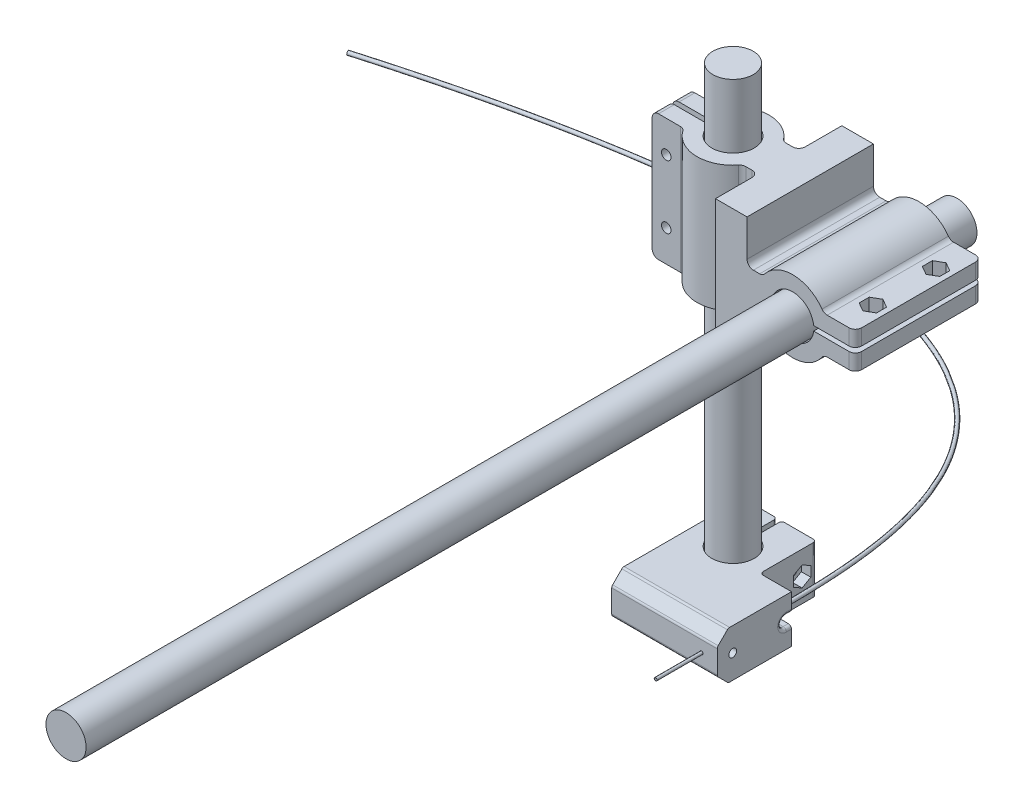
SolidWorks part; units mm, degrees
ref_plane "Front Plane" through (0, 0, 0) normal (0, 0, 1) x (1, 0, 0)
ref_plane "Top Plane" through (0, 0, 0) normal (0, 1, 0) x (1, 0, 0)
ref_plane "Right Plane" through (0, 0, 0) normal (1, 0, 0) x (0, 0, -1)
sketch "Sketch1" plane through (0, 0, 0) normal (0, 1, 0) x (1, 0, 0)
  circle A0 centre (0, 0) radius 6.4
  dimension "D1" = 12.8
extrude "Boss-Extrude1" add sketch "Sketch1" along normal blind 40 and the other way blind 100
sketch "Sketch2" plane through (0, 0, 0) normal (0, 1, 0) x (1, 0, 0)
  line L0 (-9.8437, 5.75) -> (-19.8437, 5.75)
  line L1 (-19.8437, 5.75) -> (-19.8437, 0.75)
  line L2 (0, 6.4) -> (0, 0) construction
  line L3 (-39.5441, 0) -> (14.434, 0) construction
  line L4 (9.434, -6.4) -> (14.434, -6.4)
  line L5 (-19.8437, 0.75) -> (-6.6579, 0.75)
  line L6 (-19.8437, -0.75) -> (-6.6579, -0.75)
  line L7 (-19.8437, -5.75) -> (-19.8437, -0.75)
  line L8 (-9.8437, -5.75) -> (-19.8437, -5.75)
  line L9 (14.434, -6.4) -> (14.434, 6.4)
  line L10 (14.434, 6.4) -> (9.434, 6.4)
  arc A0 (9.434, 6.4) -> (-9.8437, 5.75) centre (0, 0) ccw
  circle A1 centre (0, 0) radius 6.4 construction
  arc A2 (-6.6579, -0.75) -> (-6.6579, 0.75) centre (0, 0) ccw
  arc A3 (9.434, -6.4) -> (-9.8437, -5.75) centre (0, 0) cw
  point P13 (0, 3.2)
  point P20 (0, -3.2)
  point P21 (6.7, 0)
  dimension "D1" = 5
  dimension "D2" = 0.3
  dimension "D6" = 5
  dimension "D3" = 0.75
  dimension "D4" = 5
  dimension "D5" = 10
extrude "Boss-Extrude2" add sketch "Sketch2" along normal blind 20 and the other way blind 20 separate body
sketch "Sketch6" plane through (14.434, 0, 0) normal (1, 0, 0) x (0, 0, -1)
  line L0 (-6.4, -20) -> (6.4, -20) construction
  line L1 (-20, -20) -> (20, -20)
  line L2 (-20, -20) -> (-20, 20)
  line L3 (-20, 20) -> (20, 20)
  line L4 (20, -20) -> (20, 20)
  line L5 (-20, -20) -> (20, 20) construction
  line L6 (-20, 20) -> (20, -20) construction
  point P0 (0, 0)
  dimension "D1" = 40
extrude "Boss-Extrude6" add sketch "Sketch6" along normal blind 10
ref_plane "Plane1" through (0, 0, 0) normal (0, 0, -1) x (-1, 0, 0)
sketch "Sketch7" plane through (0, 0, 0) normal (0, 0, -1) x (-1, 0, 0)
  line L0 (0, 0) -> (-105.5276, 0) construction
  line L1 (-24.434, -6.4) -> (-29.434, -6.4)
  line L3 (-24.434, 20) -> (-24.434, -20) construction
  line L4 (-48.7116, -5.75) -> (-58.7116, -5.75)
  line L5 (-58.7116, -5.75) -> (-58.7116, -0.75)
  line L6 (-58.7116, -0.75) -> (-45.5259, -0.75)
  line L7 (-24.434, -6.4) -> (-24.434, 6.4)
  line L8 (-58.7116, 0.75) -> (-45.5259, 0.75)
  line L9 (-58.7116, 5.75) -> (-58.7116, 0.75)
  line L10 (-48.7116, 5.75) -> (-58.7116, 5.75)
  line L11 (-24.434, 6.4) -> (-29.434, 6.4)
  circle A0 centre (-38.868, 0) radius 6.4 construction
  arc A1 (-48.7116, -5.75) -> (-29.434, -6.4) centre (-38.868, 0) ccw
  arc A2 (-45.5259, -0.75) -> (-45.5259, 0.75) centre (-38.868, 0) ccw
  arc A3 (-48.7116, 5.75) -> (-29.434, 6.4) centre (-38.868, 0) cw
  point P15 (-38.868, -6.4)
  point P19 (-24.434, 0)
  point P21 (-38.868, 6.4)
  dimension "D1" = 12.8
  dimension "D2" = 5
  dimension "D4" = 0.3
  dimension "D7" = 10
  dimension "D3" = 5
  dimension "D5" = 0.75
  dimension "D6" = 5
extrude "Boss-Extrude7" add sketch "Sketch7" along normal blind 20 and the other way blind 20
fillet "Fillet4" radius 2 4 edges
fillet "Fillet5" radius 2 8 edges at (29.434, -6.4, 0) (29.434, 6.4, 0) (48.7116, 5.75, 0) (48.7116, -5.75, 0) (9.434, 0, 6.4) (9.434, 0, -6.4) (-9.8437, 0, -5.75) (-9.8437, 0, 5.75)
sketch "Sketch9" plane through (0, 0, 5.75) normal (0, 0, 1) x (1, 0, 0)
  line L0 (-10.9315, 0) -> (-19.8437, 0) construction
  line L1 (-19.8437, -20) -> (-19.8437, 20) construction
  line L2 (-15.3876, 0) -> (-15.3876, -20) construction
  line L3 (-10.9315, -20) -> (-10.9315, 20) construction
  line L4 (-19.8437, -20) -> (-10.9315, -20) construction
  circle A0 centre (-15.3876, -10) radius 1.5
  circle A1 centre (-15.3876, 0) radius 2.5 construction
  circle A2 centre (-15.3876, 10) radius 1.5
  dimension "D1" = 5
  dimension "D2" = 3
extrude "Cut-Extrude1" cut sketch "Sketch9" against normal up to surface (11.5 mm away) up to face at (-15.3876, 0, -5.75)
sketch "Sketch37" plane through (0, 0, -5.75) normal (0, 0, -1) x (-1, 0, 0)
  line L0 (18.1376, -8.4123) -> (18.1376, -11.5877)
  line L1 (12.6376, -8.4123) -> (12.6376, -11.5877)
  line L2 (18.1376, -8.4123) -> (15.3876, -6.8246)
  line L3 (15.3876, -6.8246) -> (12.6376, -8.4123)
  line L4 (12.6376, -11.5877) -> (15.3876, -13.1754)
  line L5 (15.3876, -13.1754) -> (18.1376, -11.5877)
  line L6 (12.6376, -10) -> (18.1376, -10) construction
  line L8 (10.9315, 0) -> (19.8437, 0) construction
  line L9 (10.9315, 20) -> (10.9315, -20) construction
  line L10 (19.8437, -20) -> (19.8437, 20) construction
  line L11 (12.6376, 10) -> (18.1376, 10) construction
  line L12 (15.3876, 13.1754) -> (18.1376, 11.5877)
  line L13 (12.6376, 11.5877) -> (15.3876, 13.1754)
  line L14 (15.3876, 6.8246) -> (12.6376, 8.4123)
  line L15 (18.1376, 8.4123) -> (15.3876, 6.8246)
  line L16 (12.6376, 8.4123) -> (12.6376, 11.5877)
  line L17 (18.1376, 8.4123) -> (18.1376, 11.5877)
  circle A0 centre (15.3876, -10) radius 1.25
  circle A6 centre (15.3876, -10) radius 1.5 construction
  circle A7 centre (15.3876, 10) radius 1.25
  dimension "D2" = 120
  dimension "D3" = 2.5
  dimension "D1" = 5.5
  dimension "D4" = 2.75
extrude "Cut-Extrude24" cut sketch "Sketch37" against normal up to surface (5 mm away) up to face at (-13.8876, 10, -0.75)
sketch "Sketch10" plane through (0, -5.75, 0) normal (0, -1, 0) x (-1, 0, 0)
  line L0 (-58.7116, 0) -> (-49.7995, 0) construction
  line L1 (-58.7116, -20) -> (-58.7116, 20) construction
  line L2 (-49.7995, -20) -> (-49.7995, 20) construction
  line L3 (-54.2555, 0) -> (-54.2555, 20) construction
  line L4 (-58.7116, 20) -> (-49.7995, 20) construction
  circle A0 centre (-54.2555, 0) radius 2.5 construction
  circle A1 centre (-54.2555, 10) radius 2.5
  circle A2 centre (-54.2555, -10) radius 2.5
  dimension "D1" = 5
  dimension "D2" = 5
extrude "Cut-Extrude2" cut sketch "Sketch10" against normal up to surface (11.5 mm away) up to face at (54.2555, 5.75, 0)
sketch "Sketch38" plane through (0, 5.75, 0) normal (0, 1, 0) x (1, 0, 0)
  line L0 (57.0055, 11.5877) -> (57.0055, 8.4123)
  line L1 (51.5055, 11.5877) -> (51.5055, 8.4123)
  line L2 (57.0055, 11.5877) -> (54.2555, 13.1754)
  line L3 (54.2555, 13.1754) -> (51.5055, 11.5877)
  line L4 (51.5055, 8.4123) -> (54.2555, 6.8246)
  line L5 (54.2555, 6.8246) -> (57.0055, 8.4123)
  line L6 (57.0055, 10) -> (51.5055, 10) construction
  line L7 (58.7116, 0) -> (49.7995, 0) construction
  line L8 (58.7116, -20) -> (58.7116, 20) construction
  line L9 (49.7995, 20) -> (49.7995, -20) construction
  line L10 (57.0055, -10) -> (51.5055, -10) construction
  line L11 (54.2555, -6.8246) -> (57.0055, -8.4123)
  line L12 (51.5055, -8.4123) -> (54.2555, -6.8246)
  line L13 (54.2555, -13.1754) -> (51.5055, -11.5877)
  line L14 (57.0055, -11.5877) -> (54.2555, -13.1754)
  line L15 (51.5055, -11.5877) -> (51.5055, -8.4123)
  line L16 (57.0055, -11.5877) -> (57.0055, -8.4123)
  circle A0 centre (54.2555, 10) radius 1.25
  circle A1 centre (54.2555, 10) radius 2.5 construction
  circle A2 centre (54.2555, -10) radius 1.25
  dimension "D3" = 2.5
  dimension "D1" = 5.5
  dimension "D2" = 120
  dimension "D4" = 2.75
extrude "Cut-Extrude25" cut sketch "Sketch38" against normal up to surface (5 mm away) up to face at (56.7555, 0.75, 10)
fillet "Fillet12" radius 2 8 edges at (-19.8437, 20, 3.25) (-19.8437, -20, 3.25) (-19.8437, 20, -3.25) (-19.8437, -20, -3.25) (58.7116, -3.25, -20) (58.7116, -3.25, 20) (58.7116, 3.25, -20) (58.7116, 3.25, 20)
sketch "Sketch13" plane through (0, -100, 0) normal (0, -1, 0) x (1, 0, 0)
  line L0 (11.7, -14.6579) -> (11.7, 26.7)
  line L1 (11.7, -14.6579) -> (0.75, -14.6579)
  line L2 (0, -14.6579) -> (0, 33.0338) construction
  line L3 (-11.7, 26.7) -> (11.7, 26.7)
  line L5 (0.75, -14.6579) -> (0.75, -6.6579)
  line L6 (-0.75, -14.6579) -> (-0.75, -6.6579)
  line L8 (-11.7, -14.6579) -> (-0.75, -14.6579)
  line L9 (-11.7, -14.6579) -> (-11.7, 26.7)
  arc A0 (0.75, -6.6579) -> (-0.75, -6.6579) centre (0, 0) ccw
  circle A1 centre (0, 0) radius 6.4 construction
  point P13 (6.7, 0)
  point P18 (-6.7, 0)
  point P19 (0, 6.7)
  dimension "D1" = 0.3
  dimension "D4" = 5
  dimension "D2" = 0.75
  dimension "D3" = 8
  dimension "D5" = 20
extrude "Boss-Extrude8" add sketch "Sketch13" along normal blind 7.5 and the other way blind 7.5 separate body
sketch "Sketch22" [suppressed] plane through (0, -92.5, 0) normal (0, 1, 0) x (1, 0, 0)
  line L0 (-3, -26.7) -> (-11.7, -18) construction
  line L1 (3, -26.7) -> (-3, -26.7) construction
  line L2 (11.7, -18) -> (3, -26.7) construction
  line L3 (-3, -26.7) -> (-11.7, -18)
  line L4 (3, -26.7) -> (-3, -26.7)
  line L5 (11.7, -18) -> (3, -26.7)
  line L6 (-11.7, -18) -> (-11.7, -10.7)
  line L7 (-11.7, -26.7) -> (-11.7, 14.6579) construction
  line L8 (-11.7, -10.7) -> (11.7, -10.7)
  line L9 (11.7, 14.6579) -> (11.7, -26.7) construction
  line L10 (11.7, -10.7) -> (11.7, -18)
  arc A1 (-0.75, 6.6579) -> (0.75, 6.6579) centre (0, 0) ccw construction
  point P10 (0, -6.7)
  dimension "D1" = 4
extrude "Boss-Extrude10" [suppressed] add sketch "Sketch22" along normal blind 10
sketch "Sketch23" [suppressed] plane through (0, 0, 10.7) normal (0, 0, -1) x (-1, 0, 0)
  line L0 (0, -75) -> (0, -65) construction
  line L1 (-11.7, -75) -> (11.7, -75) construction
  line L2 (-11.7, -65) -> (11.7, -65) construction
  line L3 (-11.7, -65) -> (-11.7, -75) construction
  circle A0 centre (0, -70) radius 0.5
  dimension "D1" = 1
extrude "Cut-Extrude11" [suppressed] cut sketch "Sketch23" against normal up to next
sketch "Sketch24" [suppressed] plane through (0, 0, 10.7) normal (0, 0, -1) x (-1, 0, 0)
  circle A0 centre (0, -70) radius 1.75
  dimension "D1" = 3.5
extrude "Cut-Extrude12" [suppressed] cut sketch "Sketch24" against normal blind 8
sketch "Sketch25" [suppressed] plane through (0, -65, 0) normal (0, 1, 0) x (1, 0, 0)
  line L0 (0, -26.7) -> (0, -18.7) construction
  line L1 (-3, -26.7) -> (3, -26.7) construction
  line L2 (1.75, -18.7) -> (-1.75, -18.7) construction
  circle A0 centre (0, -22.7) radius 1.45
  dimension "D1" = 2.9
extrude "Cut-Extrude13" [suppressed] cut sketch "Sketch25" against normal blind 5
sketch "Sketch26" [suppressed] plane through (0, -62.5, 0) normal (0, 1, 0) x (1, 0, 0)
  line L0 (0, -5.5763) -> (0, -13.6517) construction
  line L2 (1.75, -5.5763) -> (1.75, -13.6517)
  line L4 (-1.75, -5.5763) -> (-1.75, -13.6517)
  arc A0 (1.75, -5.5763) -> (-1.75, -5.5763) centre (0, -5.5763) ccw
  arc A1 (-1.75, -13.6517) -> (1.75, -13.6517) centre (0, -13.6517) ccw
  point P5 (0, -9.614)
  dimension "D1" = 3.5
extrude "Cut-Extrude14" [suppressed] cut sketch "Sketch26" against normal blind 5
fillet "Fillet6" radius 1 2 edges at (-11.7, -100, -14.6579) (11.7, -100, -14.6579)
fillet "Fillet7" radius 1 2 edges at (0.75, -100, -14.6579) (-0.75, -100, -14.6579)
sketch "Sketch17" plane through (-11.7, 0, 0) normal (-1, 0, 0) x (0, 0, 1)
  line L0 (-13.6579, -100) -> (-6.6579, -100) construction
  line L3 (-6.6579, -92.5) -> (-6.6579, -107.5) construction
  line L4 (-13.6579, -92.5) -> (-13.6579, -107.5) construction
  circle A0 centre (-10.1579, -100) radius 1.55
  dimension "D1" = 3.1
extrude "Cut-Extrude8" cut sketch "Sketch17" against normal up to surface (23.4 mm away) up to face at (11.7, -100, 6.5211)
sketch "Sketch18" plane through (11.7, 0, 0) normal (1, 0, 0) x (0, 0, -1)
  line L0 (12.9079, -98.4123) -> (12.9079, -101.5877)
  line L1 (7.4079, -98.4123) -> (7.4079, -101.5877)
  line L2 (12.9079, -98.4123) -> (10.1579, -96.8246)
  line L3 (10.1579, -96.8246) -> (7.4079, -98.4123)
  line L4 (7.4079, -101.5877) -> (10.1579, -103.1754)
  line L5 (10.1579, -103.1754) -> (12.9079, -101.5877)
  line L6 (12.9079, -100) -> (7.4079, -100) construction
  circle A0 centre (10.1579, -100) radius 1.25 construction
  circle A1 centre (10.1579, -100) radius 1.55 construction
  dimension "D3" = 2.5
  dimension "D1" = 5.5
  dimension "D2" = 120
  dimension "D4" = 2.75
extrude "Cut-Extrude9" cut sketch "Sketch18" against normal blind 3
sketch "Sketch19" plane through (0, -100, 0) normal (0, -1, 0) x (-1, 0, 0)
  circle A1 centre (0, 0) radius 6.4
  circle A2 centre (0, 0) radius 6.4
  dimension "D1" = 0
extrude "Boss-Extrude9" add sketch "Sketch19" along normal blind 20
fillet "Fillet9" [suppressed] radius 1
sketch "Sketch27" plane through (11.7, 0, 0) normal (1, 0, 0) x (0, 0, -1)
  line L0 (-26.7, -100) -> (13.6579, -100) construction
  line L3 (-26.7, -92.5) -> (-26.7, -107.5) construction
  line L4 (13.6579, -107.5) -> (13.6579, -92.5) construction
  line L5 (-23.2, -92.5) -> (-26.7, -96)
  line L6 (13.6579, -92.5) -> (-26.7, -92.5) construction
  line L7 (-26.7, -96) -> (-26.7, -104)
  line L8 (-23.2, -92.5) -> (-3.2, -92.5)
  line L9 (-3.2, -92.5) -> (-3.2, -107.5)
  line L10 (-23.2, -107.5) -> (-3.2, -107.5)
  line L11 (-23.2, -107.5) -> (-26.7, -104)
  point P13 (-3.2, -100)
  dimension "D1" = 45
  dimension "D2" = 20
  dimension "D3" = 4
extrude "Boss-Extrude11" add sketch "Sketch27" along normal blind 10
sketch "Sketch28" plane through (11.7, 0, 0) normal (1, 0, 0) x (0, 0, -1)
  line L0 (-26.7, -92.5) -> (-26.7, -96) construction
  line L1 (-26.7, -96) -> (-23.2, -92.5) construction
  line L2 (-23.2, -92.5) -> (-26.7, -92.5) construction
  line L3 (-26.7, -107.5) -> (-23.2, -107.5) construction
  line L4 (-23.2, -107.5) -> (-26.7, -104) construction
  line L5 (-26.7, -104) -> (-26.7, -107.5) construction
  line L6 (-26.7, -92.5) -> (-26.7, -96)
  line L7 (-26.7, -96) -> (-23.2, -92.5)
  line L8 (-23.2, -92.5) -> (-26.7, -92.5)
  line L9 (-26.7, -107.5) -> (-23.2, -107.5)
  line L10 (-23.2, -107.5) -> (-26.7, -104)
  line L11 (-26.7, -104) -> (-26.7, -107.5)
extrude "Cut-Extrude15" cut sketch "Sketch28" against normal up to next (23.4 mm away)
sketch "Sketch29" plane through (0, 0, 3.2) normal (0, 0, -1) x (-1, 0, 0)
  line L0 (-11.7, -100) -> (-21.7, -100) construction
  line L1 (-11.7, -107.5) -> (-11.7, -92.5) construction
  line L2 (-21.7, -107.5) -> (-21.7, -92.5) construction
  circle A0 centre (-16.7, -100) radius 0.5
  dimension "D1" = 1
extrude "Cut-Extrude16" cut sketch "Sketch29" against normal up to next (23.5 mm away)
sketch "Sketch30" plane through (0, 0, 3.2) normal (0, 0, -1) x (-1, 0, 0)
  circle A0 centre (-16.7, -100) radius 1.75
  dimension "D1" = 3.5
extrude "Cut-Extrude17" cut sketch "Sketch30" against normal blind 8
fillet "Fillet10" radius 1 5 edges at (5, -107.5, 23.2) (5, -104, 26.7) (5, -96, 26.7) (5, -92.5, 23.2) (11.7, -100, 3.2)
sketch "Sketch31" plane through (21.7, 0, 0) normal (1, 0, 0) x (0, 0, -1)
  line L0 (-3.2, -100) -> (-26.7, -100) construction
  line L1 (-3.2, -107.5) -> (-3.2, -92.5) construction
  line L2 (-26.7, -96.4142) -> (-26.7, -103.5858) construction
  circle A0 centre (-21.7969, -100) radius 1.25
  dimension "D1" = 2.5
extrude "Cut-Extrude18" cut sketch "Sketch31" against normal blind 5
sketch "Sketch32" plane through (21.7, 0, 0) normal (1, 0, 0) x (0, 0, -1)
  line L0 (-1.5811, -100) -> (-4.8189, -100) construction
  line L1 (-3.2, -107.5) -> (-3.2, -92.5) construction
  line L2 (-1.5811, -101.75) -> (-4.8189, -101.75)
  line L3 (-1.5811, -98.25) -> (-4.8189, -98.25)
  arc A0 (-1.5811, -101.75) -> (-1.5811, -98.25) centre (-1.5811, -100) ccw
  arc A1 (-4.8189, -98.25) -> (-4.8189, -101.75) centre (-4.8189, -100) ccw
  point P4 (-3.2, -100)
  dimension "D1" = 3.5
extrude "Cut-Extrude19" cut sketch "Sketch32" against normal blind 5
fillet "Fillet11" radius 1 3 edges at (21.7, -101.75, 4.0095) (21.7, -100, 6.5689) (21.7, -98.25, 4.0095)
sketch "Sketch39" plane through (0, 0, 0) normal (0, 0, 1) x (1, 0, 0)
  circle A0 centre (38.868, 0) radius 6.35
  dimension "D1" = 12.7
extrude "Boss-Extrude12" add sketch "Sketch39" along normal blind 250 and the other way blind 32 separate body
ref_plane "Plane3" through (0, -100, 0) normal (0, 1, 0) x (1, 0, 0)
sketch "Sketch41" plane through (0, 0, 11.2) normal (0, 0, -1) x (-1, 0, 0)
  circle A0 centre (-16.7, -100) radius 0.4
  circle A1 centre (-16.7, -100) radius 0.45
  dimension "D1" = 0.05
  dimension "D2" = 0.8
extrude "Boss-Extrude13" add sketch "Sketch41" against normal blind 30 and the other way blind 10 separate body
sketch "Sketch42" plane through (0, -100, 0) normal (0, 1, 0) x (1, 0, 0)
  line L0 (17.15, -1.2) -> (16.25, -1.2) construction
  spline S0 degree 3 poles (17.2, -11.2) (17.2, 4.4788) (20.203, 78.2682) (-56.3752, 124.8754) (-203.8417, 82.3152) knots 0 0 0 0 0.360128 1 1 1 1
sketch "Sketch43" plane through (0, 0, 11.2) normal (0, 0, -1) x (-1, 0, 0)
  circle A0 centre (-16.7, -100) radius 0.6
  dimension "D1" = 1.2
sweep "Sweep1" add profiles "Sketch43" path "Sketch42"
ref_plane "Plane4" [suppressed] through (0, 0, 36.7) normal (0, 0, 1) x (1, 0, 0)
sketch "Sketch33" plane through (14.434, 0, 0) normal (-1, 0, 0) x (0, 0, 1)
  line L0 (14.2, 20) -> (14.2, 8.4) construction
  line L1 (8.4, 20) -> (20, 20) construction
  line L2 (20, 8.4) -> (-20, 8.4) construction
  line L3 (20, 0) -> (8.4, 0) construction
  line L4 (20, 20) -> (20, -20) construction
  line L5 (8.4, 20) -> (8.4, -20) construction
  line L6 (0, 20) -> (0, -20) construction
  line L7 (-5.75, -20) -> (-0.75, -20) construction
  line L8 (-5.75, 20) -> (-0.75, 20) construction
  circle A0 centre (14.2, 14.2) radius 1.5
  circle A1 centre (14.2, -14.2) radius 1.5
  circle A2 centre (-14.2, -14.2) radius 1.5
  circle A3 centre (-14.2, 14.2) radius 1.5
  dimension "D1" = 3
extrude "Cut-Extrude20" [suppressed] cut sketch "Sketch33" against normal blind 10
sketch "Sketch44" plane through (0, 0, 11.2) normal (0, 0, -1) x (-1, 0, 0)
  circle A0 centre (-16.7, -100) radius 0.45 construction
  circle A1 centre (-16.7, -100) radius 0.4 construction
  circle A2 centre (-16.7, -100) radius 0.45
  circle A3 centre (-16.7, -100) radius 0.4
extrude "Boss-Extrude14" [suppressed] add sketch "Sketch44" along normal blind 10
sketch "Sketch34" [suppressed] plane through (14.434, 0, 0) normal (-1, 0, 0) x (0, 0, 1)
  line L0 (16.95, -12.6123) -> (16.95, -15.7877)
  line L1 (11.45, -12.6123) -> (11.45, -15.7877)
  line L2 (16.95, -12.6123) -> (14.2, -11.0246)
  line L3 (14.2, -11.0246) -> (11.45, -12.6123)
  line L4 (11.45, -15.7877) -> (14.2, -17.3754)
  line L5 (14.2, -17.3754) -> (16.95, -15.7877)
  line L6 (16.95, -14.2) -> (11.45, -14.2) construction
  line L7 (20, 0) -> (8.4, 0) construction
  line L8 (20, 20) -> (20, -20) construction
  line L9 (8.4, 20) -> (8.4, -20) construction
  line L10 (16.95, 14.2) -> (11.45, 14.2) construction
  line L11 (14.2, 17.3754) -> (16.95, 15.7877)
  line L12 (11.45, 15.7877) -> (14.2, 17.3754)
  line L13 (14.2, 11.0246) -> (11.45, 12.6123)
  line L14 (16.95, 12.6123) -> (14.2, 11.0246)
  line L15 (11.45, 12.6123) -> (11.45, 15.7877)
  line L16 (16.95, 12.6123) -> (16.95, 15.7877)
  line L17 (0, 20) -> (0, -20) construction
  line L18 (-5.75, -20) -> (-0.75, -20) construction
  line L19 (-5.75, 20) -> (-0.75, 20) construction
  line L20 (-16.95, -14.2) -> (-11.45, -14.2) construction
  line L21 (-14.2, -17.3754) -> (-16.95, -15.7877)
  line L22 (-11.45, -15.7877) -> (-14.2, -17.3754)
  line L23 (-14.2, -11.0246) -> (-11.45, -12.6123)
  line L24 (-16.95, -12.6123) -> (-14.2, -11.0246)
  line L25 (-11.45, -12.6123) -> (-11.45, -15.7877)
  line L26 (-16.95, -12.6123) -> (-16.95, -15.7877)
  line L27 (-16.95, 14.2) -> (-11.45, 14.2) construction
  line L28 (-16.95, 12.6123) -> (-16.95, 15.7877)
  line L29 (-11.45, 12.6123) -> (-11.45, 15.7877)
  line L30 (-16.95, 12.6123) -> (-14.2, 11.0246)
  line L31 (-14.2, 11.0246) -> (-11.45, 12.6123)
  line L32 (-11.45, 15.7877) -> (-14.2, 17.3754)
  line L33 (-14.2, 17.3754) -> (-16.95, 15.7877)
  circle A0 centre (14.2, -14.2) radius 1.25 construction
  circle A1 centre (14.2, -14.2) radius 1.5 construction
  circle A2 centre (14.2, 14.2) radius 1.25 construction
  circle A3 centre (-14.2, -14.2) radius 1.25 construction
  circle A4 centre (-14.2, 14.2) radius 1.25 construction
  dimension "D3" = 2.5
  dimension "D1" = 5.5
  dimension "D2" = 120
  dimension "D4" = 2.75
extrude "Cut-Extrude21" [suppressed] cut sketch "Sketch34" against normal blind 5
ref_plane "Plane2" through (19.434, 0, 0) normal (-1, 0, 0) x (0, 0, 1)
sketch "Sketch35" plane through (19.434, 0, 0) normal (-1, 0, 0) x (0, 0, 1)
  line L1 (-38.282, 26.8973) -> (38.282, 26.8973)
  line L2 (-38.282, 26.8973) -> (-38.282, -26.8973)
  line L3 (-38.282, -26.8973) -> (38.282, -26.8973)
  line L4 (38.282, 26.8973) -> (38.282, -26.8973)
  line L5 (-38.282, 26.8973) -> (38.282, -26.8973) construction
  line L6 (-38.282, -26.8973) -> (38.282, 26.8973) construction
  point P0 (0, 0)
extrude "Cut-Extrude22" [suppressed] cut sketch "Sketch35" against normal blind 76.2177
